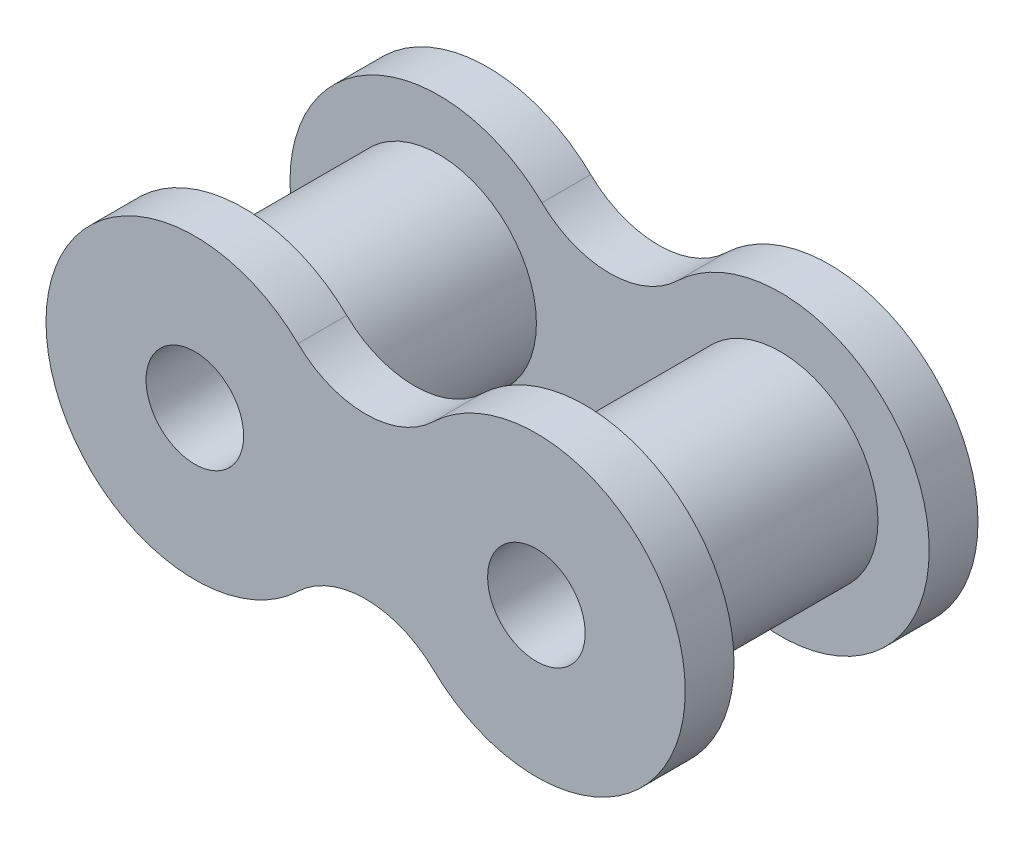
SolidWorks part; units mm, degrees
material "AISI 304"
ref_plane "Alzado" through (0, 0, 0) normal (0, 0, 1) x (1, 0, 0)
ref_plane "Planta" through (0, 0, 0) normal (0, 1, 0) x (1, 0, 0)
ref_plane "Vista lateral" through (0, 0, 0) normal (1, 0, 0) x (0, 0, -1)
sketch "Croquis1" plane through (0, 0, 0) normal (0, 0, 1) x (1, 0, 0)
  line L0 (0, 18.4869) -> (0, 3.2808) construction
  line L1 (-24.1051, 0) -> (21.976, 0) construction
  line L2 (0, -3.2808) -> (0, -17.3193) construction
  arc A6 (-2.7723, 4.3973) -> (-2.7723, -4.3973) centre (-7, 0) ccw
  circle A7 centre (-7, 0) radius 2
  circle A8 centre (7, 0) radius 2
  arc A9 (2.7723, 4.3973) -> (2.7723, -4.3973) centre (7, 0) cw
  arc A10 (-2.7723, 4.3973) -> (2.7723, 4.3973) centre (0, 7.2808) ccw
  arc A11 (-2.7723, -4.3973) -> (2.7723, -4.3973) centre (0, -7.2808) cw
  dimension "D1" = 4
  dimension "D2" = 6.1
  dimension "D3" = 4
  dimension "D4" = 2.7723
extrude "Saliente-Extruir1" add sketch "Croquis1" along normal blind 2
sketch "Croquis2" plane through (0, 0, 2) normal (0, 0, 1) x (1, 0, 0)
  circle A0 centre (7, 0) radius 2 construction
  circle A1 centre (-7, 0) radius 2 construction
  circle A2 centre (7, 0) radius 2
  circle A3 centre (-7, 0) radius 2
  arc A4 (-2.7723, 4.3973) -> (2.7723, 4.3973) centre (0, 7.2808) ccw
  arc A5 (-2.7723, 4.3973) -> (-2.7723, -4.3973) centre (-7, 0) ccw
  arc A6 (2.7723, -4.3973) -> (-2.7723, -4.3973) centre (0, -7.2808) ccw
  arc A7 (2.7723, -4.3973) -> (2.7723, 4.3973) centre (7, 0) ccw
  arc A8 (-2.7723, 4.3973) -> (2.7723, 4.3973) centre (0, 7.2808) ccw
  arc A9 (-2.7723, 4.3973) -> (-2.7723, -4.3973) centre (-7, 0) ccw
  arc A10 (2.7723, -4.3973) -> (-2.7723, -4.3973) centre (0, -7.2808) ccw
  arc A11 (2.7723, -4.3973) -> (2.7723, 4.3973) centre (7, 0) ccw
  circle A12 centre (-7, 0) radius 4
  circle A13 centre (7, 0) radius 4
  circle M5 centre (-7, 0) radius 2
  circle M10 centre (7, 0) radius 2
  dimension "D2" = 8
  dimension "D1" = 0
extrude "Saliente-Extruir2" add sketch "Croquis2" along normal blind 8 contours A12 M5 | A13 M10
ref_plane "Plano1" through (0, 0, 6) normal (0, 0, 1) x (1, 0, 0)
mirror "Simetría1" about plane through (0, 0, 6) normal (0, 0, 1) of "Saliente-Extruir1"
